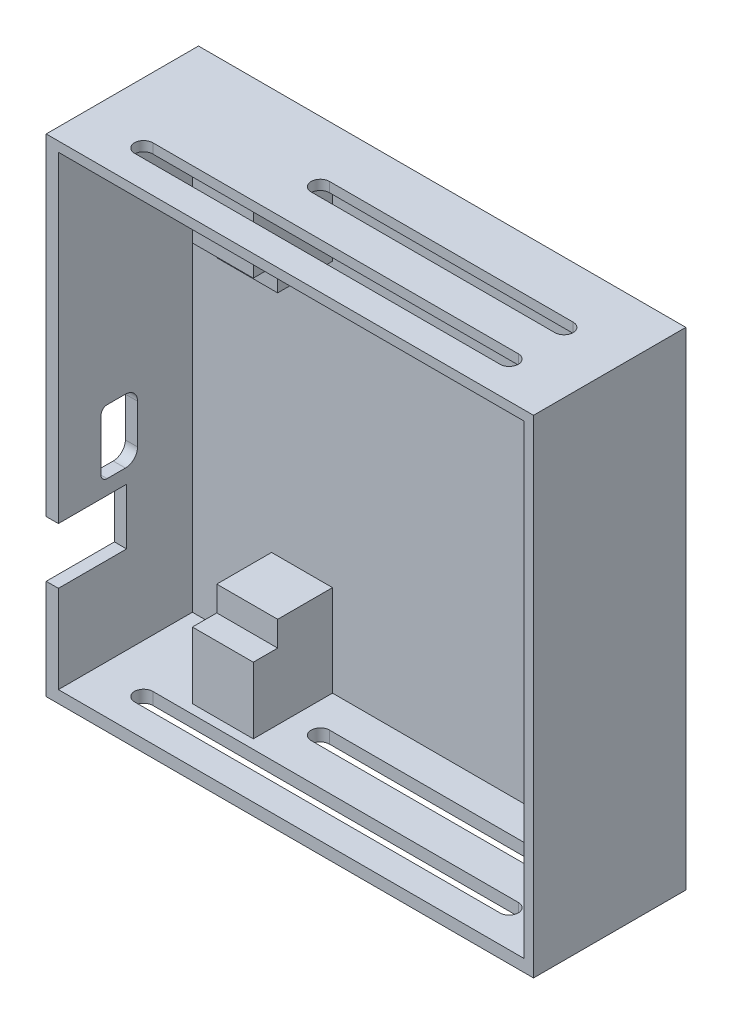
SolidWorks part; units mm, degrees
ref_plane "Plan de face" through (0, 0, 0) normal (0, 0, 1) x (1, 0, 0)
ref_plane "Plan de dessus" through (0, 0, 0) normal (0, 1, 0) x (1, 0, 0)
ref_plane "Plan de droite" through (0, 0, 0) normal (1, 0, 0) x (0, 0, -1)
sketch "Esquisse1" plane through (0, 0, 0) normal (0, 0, 1) x (1, 0, 0)
  line L1 (80, 0) -> (0, 0)
  line L2 (80, 0) -> (80, 80)
  line L3 (80, 80) -> (0, 80)
  line L4 (0, 0) -> (0, 80)
  line L5 (80, 0) -> (0, 80) construction
  line L6 (80, 80) -> (0, 0) construction
  dimension "D1" = 80
extrude "Boss.-Extru.1" add sketch "Esquisse1" along normal blind 25
sketch "Esquisse2" plane through (0, 0, 25) normal (0, 0, 1) x (1, 0, 0)
  line L1 (78.4, 78.4) -> (2, 78.4)
  line L2 (78.4, 78.4) -> (78.4, 2)
  line L3 (78.4, 2) -> (2, 2)
  line L4 (2, 78.4) -> (2, 2)
  line L5 (78.4, 78.4) -> (2, 2) construction
  line L6 (78.4, 2) -> (2, 78.4) construction
  point P0 (40.2, 40.2)
  dimension "D1" = 76.4
  dimension "D2" = 76.4
extrude "Enlèv. mat.-Extru.3" cut sketch "Esquisse2" against normal blind 22
sketch "Esquisse3" plane through (0, 0, 3) normal (0, 0, 1) x (1, 0, 0)
  line L0 (78.4, 2) -> (78.4, 78.4) construction
  line L1 (25, 17) -> (15, 17)
  line L2 (25, 17) -> (25, 2)
  line L3 (25, 2) -> (15, 2)
  line L4 (15, 17) -> (15, 2)
  line L5 (78.4, 44.6885) -> (68.4, 44.6885)
  line L6 (78.4, 44.6885) -> (78.4, 34.6885)
  line L7 (78.4, 34.6885) -> (68.4, 34.6885)
  line L8 (68.4, 44.6885) -> (68.4, 34.6885)
  line L9 (78.4, 78.4) -> (2, 78.4) construction
  line L10 (25, 78.4) -> (15, 78.4)
  line L11 (25, 78.4) -> (25, 63.4)
  line L12 (25, 63.4) -> (15, 63.4)
  line L13 (15, 78.4) -> (15, 63.4)
  line L14 (2, 2) -> (78.4, 2) construction
  dimension "D1" = 10
  dimension "D2" = 15
  dimension "D3" = 10
  dimension "D4" = 10
  dimension "D5" = 15
  dimension "D6" = 10
extrude "Boss.-Extru.2" add sketch "Esquisse3" along normal blind 9
sketch "Esquisse4" plane through (0, 0, 12) normal (0, 0, 1) x (1, 0, 0)
  line L0 (25, 63.4) -> (25, 78.4) construction
  line L1 (25, 2) -> (15, 2)
  line L2 (25, 2) -> (25, 12.9)
  line L3 (25, 12.9) -> (15, 12.9)
  line L4 (15, 2) -> (15, 12.9)
  line L6 (15, 78.4) -> (25, 78.4)
  line L7 (15, 78.4) -> (15, 67.5)
  line L8 (15, 67.5) -> (25, 67.5)
  line L9 (25, 78.4) -> (25, 67.5)
  line L12 (78.4, 44.6885) -> (72.4, 44.6885)
  line L13 (78.4, 44.6885) -> (78.4, 34.6885)
  line L14 (78.4, 34.6885) -> (72.4, 34.6885)
  line L15 (72.4, 44.6885) -> (72.4, 34.6885)
  dimension "D1" = 10.9
  dimension "D2" = 10.9
  dimension "D3" = 6
extrude "Boss.-Extru.3" add sketch "Esquisse4" along normal blind 4
sketch "Esquisse5" plane through (0, 0, 0) normal (-1, 0, 0) x (0, 0, 1)
  line L0 (25, 0) -> (0, 0) construction
  line L1 (13.8, 25.6) -> (25, 25.6)
  line L2 (13.8, 25.6) -> (13.8, 16.4)
  line L3 (13.8, 16.4) -> (25, 16.4)
  line L4 (25, 25.6) -> (25, 16.4)
  line L5 (13.8, 25.6) -> (25, 16.4) construction
  line L6 (13.8, 16.4) -> (25, 25.6) construction
  line L7 (18, 38.5) -> (12, 38.5)
  line L8 (18, 38.5) -> (18, 28)
  line L9 (18, 28) -> (12, 28)
  line L10 (12, 38.5) -> (12, 28)
  line L11 (18, 38.5) -> (12, 28) construction
  line L12 (18, 28) -> (12, 38.5) construction
  line L13 (25, 80) -> (25, 0) construction
  point P0 (19.4, 21)
  point P5 (15, 33.25)
  dimension "D1" = 11.2
  dimension "D2" = 9.2
  dimension "D3" = 6
  dimension "D4" = 10.5
  dimension "D5" = 16.4
  dimension "D6" = 28
  dimension "D7" = 7
  dimension "D8" = 2.4
extrude "Enlèv. mat.-Extru.4" cut sketch "Esquisse5" against normal blind 10
fillet "Congé2" radius 2 2 edges at (1, 28, 12) (1, 38.5, 12)
fillet "Congé3" radius 1 2 edges at (1, 28, 18) (1, 38.5, 18)
sketch "Esquisse8" plane through (0, 0, 0) normal (-1, 0, 0) x (0, 0, 1)
  spline S0 degree 3 poles (7.3132, 65.8332) (7.489, 65.7124) (7.8041, 65.496) (8.4873, 65.2836) (8.9811, 65.226) (9.3077, 65.1879) knots 0 0 0 0 0.299076 0.53634 1 1 1 1
  spline S1 degree 3 poles (9.3077, 65.1879) (9.7678, 65.1373) (10.7192, 65.0327) (12.1094, 64.1793) (12.6843, 63.2245) (13.0033, 62.6948) knots 0 0 0 0 0.294281 0.608472 1 1 1 1
  spline S2 degree 3 poles (13.0033, 62.6948) (13.0329, 62.6354) (13.0948, 62.5111) (13.1865, 62.3139) (13.2476, 62.1758) (13.2793, 62.1041) knots 0 0 0 0 0.30514 0.639136 1 1 1 1
  spline S3 degree 3 poles (13.2793, 62.1041) (13.2369, 62.0856) (13.0513, 62.0046) (12.5663, 61.8654) (12.2101, 61.5749) (11.9768, 61.3846) knots 0 0 0 0 0.092718 0.405716 1 1 1 1
  spline S4 degree 3 poles (11.9768, 61.3846) (12.2338, 61.501) (12.6403, 61.6852) (13.1574, 61.8624) (13.3811, 61.7947) (13.4433, 61.7759) knots 0 0 0 0 0.553685 0.875787 1 1 1 1
  spline S5 degree 3 poles (13.4433, 61.7759) (13.7742, 60.9156) (14.4639, 59.1226) (15.3298, 56.5647) (15.9351, 54.8923) (16.2004, 54.1596) knots 0 0 0 0 0.341315 0.711412 1 1 1 1
  spline S6 degree 3 poles (16.2004, 54.1596) (16.4388, 53.6038) (16.8799, 52.5756) (17.7426, 51.2696) (18.3324, 50.5184) (18.6055, 50.1707) knots 0 0 0 0 0.387195 0.716321 1 1 1 1
  spline S7 degree 3 poles (18.6055, 50.1707) (18.2809, 50.443) (17.2558, 51.3033) (15.6146, 52.7654) (14.4277, 54.081) (13.8539, 54.7169) knots 0 0 0 0 0.193087 0.609951 1 1 1 1
  spline S8 degree 3 poles (13.8539, 54.7169) (13.7708, 54.822) (13.5602, 55.0881) (13.1751, 55.5512) (12.8791, 55.914) (12.713, 56.1177) knots 0 0 0 0 0.222488 0.563484 1 1 1 1
  spline S9 degree 3 poles (12.713, 56.1177) (12.6891, 56.2292) (12.6056, 56.6191) (12.5386, 57.4334) (12.5297, 58.1337) (12.5244, 58.5495) knots 0 0 0 0 0.139881 0.489306 1 1 1 1
  spline S10 degree 3 poles (12.5244, 58.5495) (12.4757, 58.1954) (12.3897, 57.5687) (12.461, 56.8358) (12.5048, 56.4619) (12.5168, 56.36) knots 0 0 0 0 0.485971 0.859909 1 1 1 1
  spline S11 degree 3 poles (12.5168, 56.36) (12.2201, 56.7319) (11.602, 57.5071) (10.6965, 58.7098) (10.1286, 59.5682) (9.8453, 59.9964) knots 0 0 0 0 0.316155 0.658882 1 1 1 1
  spline S12 degree 3 poles (9.8453, 59.9964) (9.8116, 60.1159) (9.7177, 60.4485) (9.8247, 61.1254) (9.8866, 61.6666) (9.9236, 61.9909) knots 0 0 0 0 0.183614 0.510917 1 1 1 1
  spline S13 degree 3 poles (9.9236, 61.9909) (9.7972, 61.7028) (9.5915, 61.2346) (9.5336, 60.6531) (9.5725, 60.3966) (9.5819, 60.334) knots 0 0 0 0 0.547076 0.889409 1 1 1 1
  spline S14 degree 3 poles (9.5819, 60.334) (9.359, 60.6953) (8.9256, 61.3973) (8.3715, 62.4532) (8.1116, 63.1732) (7.9878, 63.5161) knots 0 0 0 0 0.357022 0.693778 1 1 1 1
  spline S15 degree 3 poles (7.9878, 63.5161) (7.9337, 63.8524) (7.851, 64.3664) (7.7305, 65.142) (7.4272, 65.4517) (7.2546, 65.6278) knots 0 0 0 0 0.449394 0.686727 1 1 1 1
  spline S16 degree 3 poles (7.2546, 65.6278) (7.2462, 65.6498) (7.2256, 65.7034) (7.2619, 65.7802) (7.2989, 65.8184) (7.3132, 65.8332) knots 0 0 0 0 0.298494 0.728385 1 1 1 1
  spline S17 degree 3 poles (5.8687, 66.977) (5.8842, 66.9492) (5.9347, 66.8582) (6.033, 66.7026) (6.0984, 66.5652) (6.1327, 66.4931) knots 0 0 0 0 0.173192 0.566196 1 1 1 1
  spline S18 degree 3 poles (6.1327, 66.4931) (6.1602, 66.4702) (6.2619, 66.3853) (6.4784, 66.2222) (6.6715, 66.0881) (6.7853, 66.0091) knots 0 0 0 0 0.132138 0.488781 1 1 1 1
  spline S19 degree 3 poles (6.7853, 66.0091) (7.5865, 65.3157) (9.4, 63.7462) (11.7414, 60.8453) (13.8463, 57.8441) (15.265, 55.1001) (16.3337, 52.7227) (17.367, 51.5047) (17.9015, 50.8746) knots 0 0 0 0 0.167785 0.379771 0.589081 0.748039 0.86967 1 1 1 1
  spline S20 degree 3 poles (17.9015, 50.8746) (17.3561, 51.5308) (16.2935, 52.8094) (15.2755, 55.2283) (13.9339, 57.8853) (11.9336, 60.7458) (9.6285, 63.6519) (7.7964, 65.3332) (6.9319, 66.1265) knots 0 0 0 0 0.134488 0.262039 0.413324 0.606279 0.814216 1 1 1 1
  spline S21 degree 3 poles (6.9319, 66.1265) (6.8424, 66.1977) (6.5853, 66.402) (6.2341, 66.6894) (5.9673, 66.8994) (5.8687, 66.977) knots 0 0 0 0 0.252043 0.723507 1 1 1 1
extrude "Enlèv. mat.-Extru.5" cut sketch "Esquisse8" against normal blind 0.5 contours S20 S19 S15 S14 S13 S12 S11 S10 S9 S8 S7 S6 S5 S4 S3 S2 S1 S0 S16
sketch "Esquisse11" plane through (0, 0, 0) normal (-1, 0, 0) x (0, 0, 1)
  spline S0 degree 3 poles (7.3026, 65.8128) (7.4783, 65.6921) (7.7934, 65.4757) (8.4767, 65.2633) (8.9704, 65.2057) (9.297, 65.1676) knots 0 0 0 0 0.299076 0.53634 1 1 1 1
  spline S1 degree 3 poles (9.297, 65.1676) (9.7572, 65.117) (10.7086, 65.0124) (12.0987, 64.159) (12.6737, 63.2042) (12.9927, 62.6745) knots 0 0 0 0 0.294281 0.608472 1 1 1 1
  spline S2 degree 3 poles (12.9927, 62.6745) (13.0222, 62.6151) (13.0841, 62.4907) (13.1758, 62.2936) (13.2369, 62.1555) (13.2687, 62.0838) knots 0 0 0 0 0.30514 0.639136 1 1 1 1
  spline S3 degree 3 poles (13.2687, 62.0838) (13.2262, 62.0653) (13.0407, 61.9843) (12.5556, 61.8451) (12.1994, 61.5546) (11.9661, 61.3643) knots 0 0 0 0 0.092718 0.405716 1 1 1 1
  spline S4 degree 3 poles (11.9661, 61.3643) (12.2231, 61.4807) (12.6296, 61.6649) (13.1467, 61.8421) (13.3704, 61.7744) (13.4326, 61.7556) knots 0 0 0 0 0.553685 0.875787 1 1 1 1
  spline S5 degree 3 poles (13.4326, 61.7556) (13.7635, 60.8953) (14.4532, 59.1023) (15.3191, 56.5443) (15.9245, 54.872) (16.1897, 54.1393) knots 0 0 0 0 0.341315 0.711412 1 1 1 1
  spline S6 degree 3 poles (16.1897, 54.1393) (16.4281, 53.5835) (16.8692, 52.5552) (17.7319, 51.2493) (18.3217, 50.4981) (18.5948, 50.1504) knots 0 0 0 0 0.387195 0.716321 1 1 1 1
  spline S7 degree 3 poles (18.5948, 50.1504) (18.2703, 50.4227) (17.2451, 51.283) (15.6039, 52.7451) (14.417, 54.0607) (13.8432, 54.6966) knots 0 0 0 0 0.193087 0.609951 1 1 1 1
  spline S8 degree 3 poles (13.8432, 54.6966) (13.7601, 54.8017) (13.5495, 55.0678) (13.1644, 55.5308) (12.8684, 55.8937) (12.7023, 56.0974) knots 0 0 0 0 0.222488 0.563484 1 1 1 1
  spline S9 degree 3 poles (12.7023, 56.0974) (12.6784, 56.2089) (12.5949, 56.5988) (12.5279, 57.4131) (12.519, 58.1134) (12.5137, 58.5292) knots 0 0 0 0 0.139881 0.489306 1 1 1 1
  spline S10 degree 3 poles (12.5137, 58.5292) (12.4651, 58.1751) (12.379, 57.5484) (12.4503, 56.8155) (12.4941, 56.4416) (12.5061, 56.3397) knots 0 0 0 0 0.485971 0.859909 1 1 1 1
  spline S11 degree 3 poles (12.5061, 56.3397) (12.2095, 56.7116) (11.5913, 57.4868) (10.6858, 58.6895) (10.1179, 59.5479) (9.8347, 59.9761) knots 0 0 0 0 0.316155 0.658882 1 1 1 1
  spline S12 degree 3 poles (9.8347, 59.9761) (9.8009, 60.0956) (9.707, 60.4282) (9.814, 61.1051) (9.8759, 61.6463) (9.913, 61.9706) knots 0 0 0 0 0.183614 0.510917 1 1 1 1
  spline S13 degree 3 poles (9.913, 61.9706) (9.7865, 61.6825) (9.5808, 61.2142) (9.523, 60.6328) (9.5618, 60.3763) (9.5713, 60.3137) knots 0 0 0 0 0.547076 0.889409 1 1 1 1
  spline S14 degree 3 poles (9.5713, 60.3137) (9.3483, 60.6749) (8.915, 61.377) (8.3609, 62.4329) (8.1009, 63.1529) (7.9772, 63.4957) knots 0 0 0 0 0.357022 0.693778 1 1 1 1
  spline S15 degree 3 poles (7.9772, 63.4957) (7.923, 63.8321) (7.8403, 64.3461) (7.7198, 65.1217) (7.4165, 65.4314) (7.2439, 65.6075) knots 0 0 0 0 0.449394 0.686727 1 1 1 1
  spline S16 degree 3 poles (7.2439, 65.6075) (7.2355, 65.6295) (7.2149, 65.6831) (7.2512, 65.7599) (7.2882, 65.7981) (7.3026, 65.8128) knots 0 0 0 0 0.298494 0.728385 1 1 1 1
  spline S17 degree 3 poles (5.858, 66.9567) (5.8735, 66.9289) (5.924, 66.8379) (6.0223, 66.6822) (6.0877, 66.5449) (6.122, 66.4728) knots 0 0 0 0 0.173192 0.566196 1 1 1 1
  spline S18 degree 3 poles (6.122, 66.4728) (6.1495, 66.4498) (6.2512, 66.365) (6.4677, 66.2019) (6.6608, 66.0678) (6.7746, 65.9888) knots 0 0 0 0 0.132138 0.488781 1 1 1 1
  spline S19 degree 3 poles (6.7746, 65.9888) (7.5758, 65.2954) (9.3893, 63.7259) (11.7307, 60.825) (13.8356, 57.8238) (15.2543, 55.0798) (16.323, 52.7024) (17.3563, 51.4844) (17.8908, 50.8543) knots 0 0 0 0 0.167785 0.379771 0.589081 0.748039 0.86967 1 1 1 1
  spline S20 degree 3 poles (17.8908, 50.8543) (17.3454, 51.5105) (16.2828, 52.7891) (15.2649, 55.2079) (13.9232, 57.865) (11.9229, 60.7255) (9.6179, 63.6316) (7.7858, 65.3128) (6.9213, 66.1062) knots 0 0 0 0 0.134488 0.262039 0.413324 0.606279 0.814216 1 1 1 1
  spline S21 degree 3 poles (6.9213, 66.1062) (6.8317, 66.1773) (6.5747, 66.3817) (6.2234, 66.6691) (5.9566, 66.8791) (5.858, 66.9567) knots 0 0 0 0 0.252043 0.723507 1 1 1 1
extrude "Enlèv. mat.-Extru.6" cut sketch "Esquisse11" against normal blind 0.5 contours S20 S21 S17 S18 S19 S15 S16
sketch "Esquisse12" plane through (0, 0, 0) normal (0, -1, 0) x (-1, 0, 0)
  line L0 (-10, -19) -> (-70, -19) construction
  line L1 (-10, -20.5) -> (-70, -20.5)
  line L2 (-10, -17.5) -> (-70, -17.5)
  line L3 (-70, -10) -> (-30, -10) construction
  line L4 (-70, -8.5) -> (-30, -8.5)
  line L5 (-70, -11.5) -> (-30, -11.5)
  line L6 (-80, -25) -> (-80, 0) construction
  line L7 (0, -25) -> (0, 0) construction
  line L8 (0, -25) -> (-80, -25) construction
  line L9 (0, 0) -> (-80, 0) construction
  arc A0 (-10, -20.5) -> (-10, -17.5) centre (-10, -19) ccw
  arc A1 (-70, -17.5) -> (-70, -20.5) centre (-70, -19) ccw
  arc A2 (-70, -8.5) -> (-70, -11.5) centre (-70, -10) ccw
  arc A3 (-30, -11.5) -> (-30, -8.5) centre (-30, -10) ccw
  point P2 (-40, -19)
  point P7 (-50, -10)
  dimension "D1" = 3
  dimension "D2" = 3
  dimension "D3" = 10
  dimension "D4" = 10
  dimension "D5" = 30
  dimension "D6" = 10
  dimension "D7" = 6
  dimension "D8" = 10
  dimension "D9" = 40
  dimension "D10" = 60
extrude "Enlèv. mat.-Extru.7" cut sketch "Esquisse12" against normal blind 2
sketch "Esquisse14" plane through (0, 80, 0) normal (0, 1, 0) x (1, 0, 0)
  line L0 (70, -19) -> (10, -19) construction
  line L1 (70, -20.5) -> (10, -20.5)
  line L2 (70, -17.5) -> (10, -17.5)
  line L3 (70, -10) -> (30, -10) construction
  line L4 (70, -11.5) -> (30, -11.5)
  line L5 (70, -8.5) -> (30, -8.5)
  line L6 (80, -25) -> (80, 0) construction
  line L7 (0, -25) -> (0, 0) construction
  line L8 (80, 0) -> (0, 0) construction
  line L9 (80, -25) -> (0, -25) construction
  arc A0 (70, -20.5) -> (70, -17.5) centre (70, -19) ccw
  arc A1 (10, -17.5) -> (10, -20.5) centre (10, -19) ccw
  arc A2 (70, -11.5) -> (70, -8.5) centre (70, -10) ccw
  arc A3 (30, -8.5) -> (30, -11.5) centre (30, -10) ccw
  point P2 (40, -19)
  point P7 (50, -10)
  dimension "D1" = 3
  dimension "D2" = 3
  dimension "D3" = 10
  dimension "D4" = 10
  dimension "D5" = 30
  dimension "D6" = 10
  dimension "D7" = 10
  dimension "D8" = 6
extrude "Enlèv. mat.-Extru.8" cut sketch "Esquisse14" against normal blind 2
